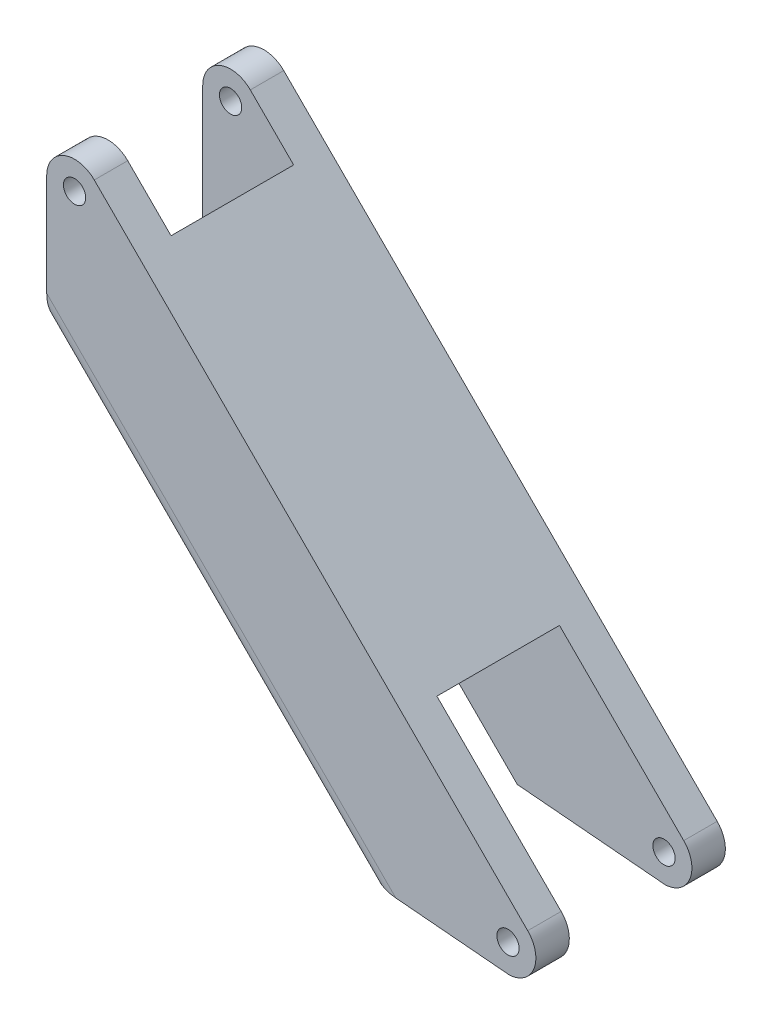
SolidWorks part; units mm, degrees
ref_plane "Спереди" through (0, 0, 0) normal (0, 0, 1) x (1, 0, 0)
ref_plane "Сверху" through (0, 0, 0) normal (0, 1, 0) x (1, 0, 0)
ref_plane "Справа" through (0, 0, 0) normal (1, 0, 0) x (0, 0, -1)
sketch "Sketch1" plane through (0, 0, 0) normal (0, 0, 1) x (1, 0, 0)
  line L0 (5.5175, 34.7934) -> (30.9732, 9.3377) construction
  line L5 (-5.0237, 27.2991) -> (9.5611, 12.7142)
  line L6 (22.7253, 14.05) -> (0.4801, 15.9962) construction
  line L7 (22.8388, 11.5526) -> (9.5611, 12.7142)
  line L8 (-16.1655, 52.9409) -> (22.7253, 14.05) construction
  line L9 (-14.3978, 54.7087) -> (5.5175, 34.7934)
  line L11 (-16.1655, 52.9409) -> (-21.5982, 52.9409) construction
  line L12 (-18.6655, 52.9409) -> (-18.6655, 40.9409)
  line L13 (-18.6655, 40.9409) -> (-5.0237, 27.2991)
  line L15 (5.5175, 34.7934) -> (24.4931, 15.8178)
  line L33 (22.7253, 14.05) -> (-16.1655, 52.9409) construction
  circle A0 centre (-16.1655, 52.9409) radius 1
  circle A2 centre (22.7253, 14.05) radius 1
  arc A3 (-14.3978, 54.7087) -> (-18.6655, 52.9409) centre (-16.1655, 52.9409) ccw
  arc A5 (22.1799, 11.6102) -> (24.4931, 15.8178) centre (22.7253, 14.05) ccw
  point P1 (-9.2596, 44.9982)
  dimension "D6" = 2
  dimension "D4" = 40
  dimension "D1" = 55
  dimension "D2" = 12
  dimension "D3" = 135
extrude "Boss-Extrude1" add sketch "Sketch1" along normal blind 17
ref_plane "Plane1" through (0, 0, 14) normal (0, 0, 1) x (1, 0, 0)
sketch "Sketch2" plane through (20.1554, 20.1554, 0) normal (0.7071, 0.7071, 0) x (0.7071, -0.7071, 0)
  line L6 (-26.0845, -14) -> (26.0845, -14) construction
  line L8 (-48.8656, -8.5) -> (-9.6849, -8.5) construction
  line L9 (-48.8656, -17) -> (-48.8656, 0) construction
  line L11 (-31.4609, -3) -> (-3.2579, -3) construction
  line L12 (-22.4013, -3) -> (-25.4013, -3)
  line L14 (-22.4013, -3) -> (31.2367, -3)
  line L15 (-25.4013, -3) -> (-25.4013, -14)
  line L16 (-25.4013, -14) -> (31.2367, -14)
  line L17 (31.2367, -14) -> (31.2367, -3)
  line L18 (-38.3661, 0) -> (-67.07, 0) construction
  line L21 (-43.3661, -3) -> (-60.6964, -3)
  line L22 (-60.6964, -3) -> (-60.6964, -14)
  line L23 (-60.6964, -14) -> (-43.3661, -14)
  line L24 (-43.3661, -14) -> (-43.3661, -3)
  dimension "D1" = 3
extrude "Cut-Extrude1" cut sketch "Sketch2" against normal blind 17
sketch "Sketch3" plane through (-30.6644, 30.6644, 0) normal (-0.7071, 0.7071, 0) x (0, 0, 1)
  line L0 (3, 24.2363) -> (14, 24.2363)
  line L1 (14, -26.0845) -> (14, 26.0845) construction
  line L2 (17, 24.2363) -> (14, 24.2363) construction
  line L3 (14, 24.2363) -> (14, 12.6246)
  line L4 (3, 24.2363) -> (3, 12.6246)
  line L5 (3, 12.6246) -> (14, 12.6246)
extrude "Cut-Extrude2" cut sketch "Sketch3" against normal through all
sketch "Sketch4" plane through (20.1554, 20.1554, 0) normal (0.7071, 0.7071, 0) x (0, 0, -1)
  line L0 (-14, 25.4013) -> (-3, 25.4013)
  line L1 (-3, 25.4013) -> (-3, 9.6334)
  line L2 (-3, -6.1344) -> (-3, 25.4013) construction
  line L3 (-3, 9.6334) -> (-14, 9.6334)
  line L4 (-14, 25.4013) -> (-14, -6.1344) construction
  line L5 (-14, 9.6334) -> (-14, 25.4013)
extrude "Boss-Extrude2" add sketch "Sketch4" against normal blind 2
fillet "Fillet1" radius 2 2 edges at (-4.5522, 26.8276, 17) (-4.5522, 26.8276, 0)
